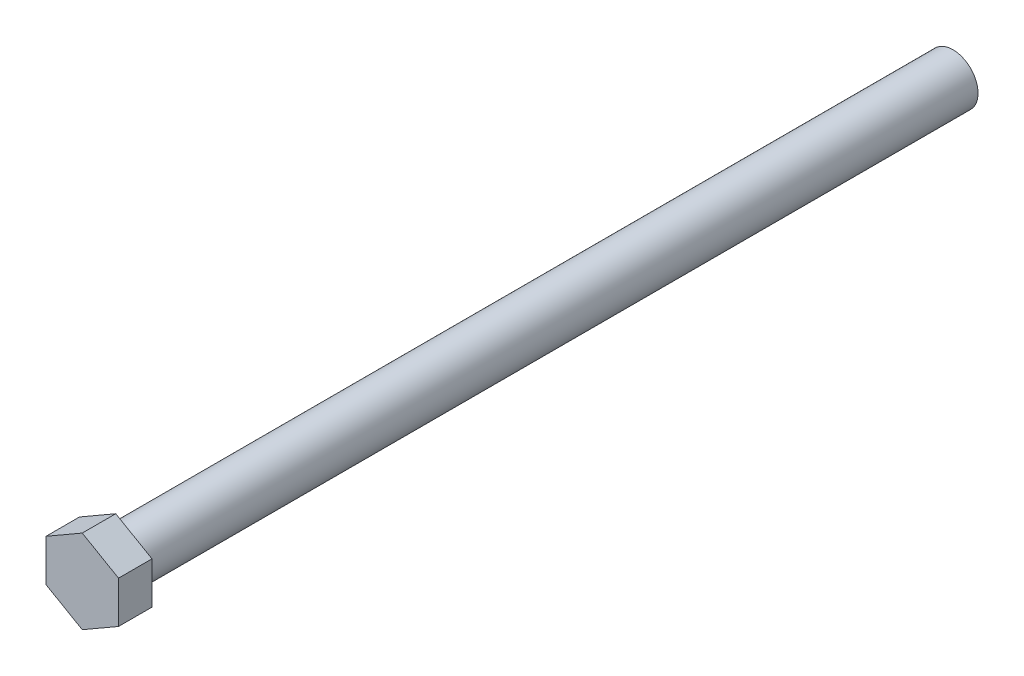
SolidWorks part; units mm, degrees
ref_plane "Front Plane" through (0, 0, 0) normal (1, 0, 0) x (0, 1, 0)
ref_plane "Top Plane" through (0, 0, 0) normal (0, 0, 1) x (0, 1, 0)
ref_plane "Right Plane" through (0, 0, 0) normal (0, 1, 0) x (-1, 0, 0)
sketch "Sketch1" plane through (0, 0, 0) normal (0, 0, 1) x (0, 1, 0)
  line L1 (2.5, 4.3301) -> (-2.5, 4.3301)
  line L2 (-2.5, 4.3301) -> (-5, 0)
  line L3 (-5, 0) -> (-2.5, -4.3301)
  line L4 (-2.5, -4.3301) -> (2.5, -4.3301)
  line L5 (2.5, -4.3301) -> (5, 0)
  line L6 (5, 0) -> (2.5, 4.3301)
  circle A0 centre (0, 0) radius 4.3301 construction
  point P1 (2.499, -4.3301)
  point P10 (0, 0)
  dimension "D1" = 10
extrude "Boss-Extrude1" add sketch "Sketch1" along normal blind 4
sketch "Sketch2" plane through (0, 0, 0) normal (0, 0, -1) x (1, 0, 0)
  circle A0 centre (0, 0) radius 3
  dimension "D1" = 6
extrude "Boss-Extrude2" add sketch "Sketch2" along normal blind 100
